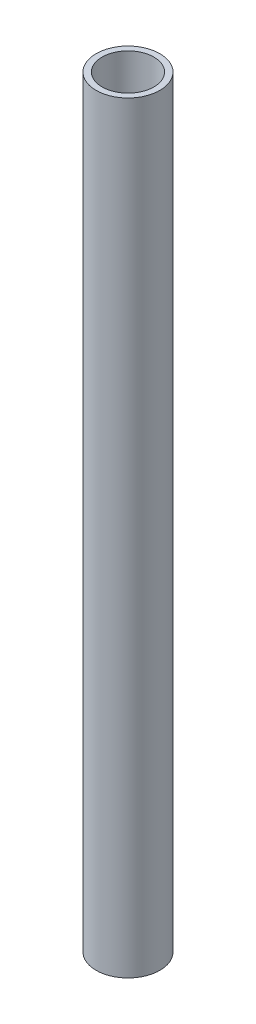
SolidWorks part; units mm, degrees
material "201 Annealed Stainless Steel (SS)"
ref_plane "Front Plane" through (0, 0, 0) normal (0, 0, 1) x (1, 0, 0)
ref_plane "Top Plane" through (0, 0, 0) normal (0, 1, 0) x (1, 0, 0)
ref_plane "Right Plane" through (0, 0, 0) normal (1, 0, 0) x (0, 0, -1)
sketch "Sketch1" plane through (0, 0, 0) normal (0, 1, 0) x (1, 0, 0)
  circle A0 centre (0, 0) radius 10.45
  dimension "D1" = 20.9
extrude "Boss-Extrude1" add sketch "Sketch1" along normal blind 250 contours A0
sketch "Sketch2" plane through (0, 0, 0) normal (0, -1, 0) x (-1, 0, 0)
  circle A0 centre (0, 0) radius 8.5
  dimension "D1" = 17
extrude "Cut-Extrude1" cut sketch "Sketch2" against normal through all
